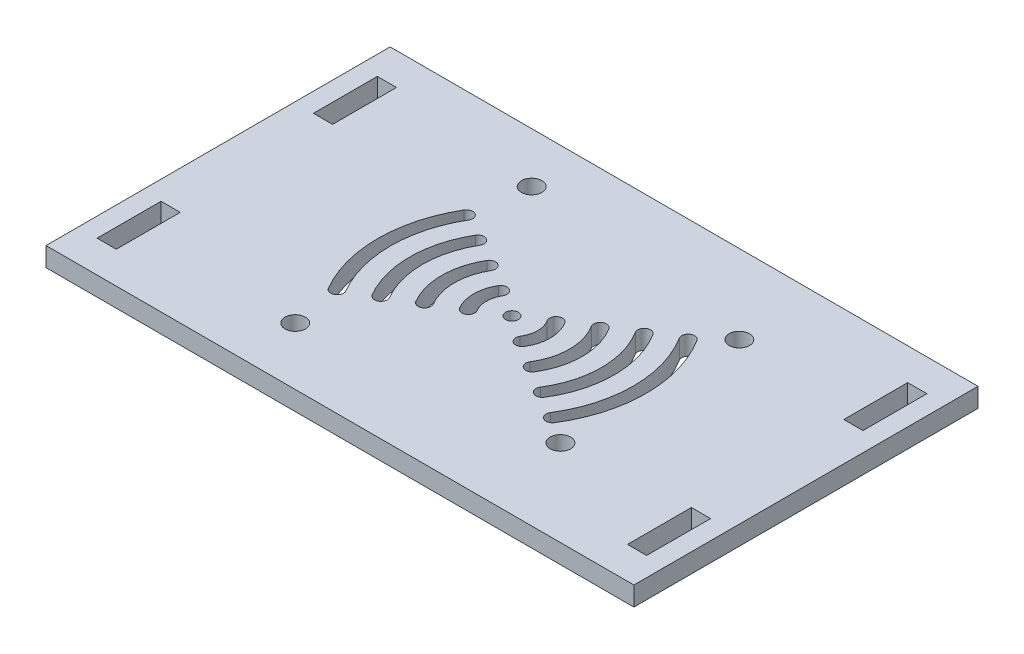
SolidWorks part; units mm, degrees
material "ABS"
ref_plane "Front Plane" through (0, 0, 0) normal (0, 0, 1) x (1, 0, 0)
ref_plane "Top Plane" through (0, 0, 0) normal (0, 1, 0) x (1, 0, 0)
ref_plane "Right Plane" through (0, 0, 0) normal (1, 0, 0) x (0, 0, -1)
sketch "Sketch1" plane through (0, 0, 0) normal (0, 1, 0) x (1, 0, 0)
  line L0 (0, 53.85) -> (92, 0) construction
  line L1 (0, 0) -> (92, 0)
  line L2 (0, 0) -> (0, 53.85)
  line L3 (0, 53.85) -> (92, 53.85)
  line L4 (92, 0) -> (92, 53.85)
  line L5 (3, 48.85) -> (6, 48.85)
  line L6 (3, 48.85) -> (3, 38.85)
  line L7 (3, 38.85) -> (6, 38.85)
  line L8 (6, 48.85) -> (6, 38.85)
  line L9 (3, 15) -> (6, 15)
  line L10 (3, 15) -> (3, 5)
  line L11 (3, 5) -> (6, 5)
  line L12 (6, 15) -> (6, 5)
  line L13 (92, 53.85) -> (0, 0) construction
  line L15 (86, 15) -> (86, 5)
  line L16 (89, 5) -> (86, 5)
  line L17 (89, 15) -> (89, 5)
  line L18 (89, 15) -> (86, 15)
  line L19 (86, 48.85) -> (86, 38.85)
  line L20 (89, 38.85) -> (86, 38.85)
  line L21 (89, 48.85) -> (89, 38.85)
  line L22 (89, 48.85) -> (86, 48.85)
  circle A0 centre (46, 26.925) radius 1
  arc A1 (41.6849, 29.4508) -> (41.6849, 24.3992) centre (46, 26.925) ccw construction
  arc A2 (40.8218, 29.9559) -> (40.8218, 23.8941) centre (46, 26.925) ccw
  arc A3 (42.5479, 28.9456) -> (42.5479, 24.9044) centre (46, 26.925) ccw
  arc A4 (42.5479, 28.9456) -> (40.8218, 29.9559) centre (41.6849, 29.4508) ccw
  arc A5 (40.8218, 23.8941) -> (42.5479, 24.9044) centre (41.6849, 24.3992) ccw
  arc A6 (37.3697, 21.8735) -> (37.3697, 31.9765) centre (46, 26.925) cw construction
  arc A7 (36.5067, 32.4817) -> (36.5067, 21.3683) centre (46, 26.925) ccw
  arc A8 (38.2327, 31.4714) -> (38.2327, 22.3786) centre (46, 26.925) ccw
  arc A9 (38.2327, 31.4714) -> (36.5067, 32.4817) centre (37.3697, 31.9765) ccw
  arc A10 (36.5067, 21.3683) -> (38.2327, 22.3786) centre (37.3697, 21.8735) ccw
  arc A11 (33.0546, 19.3477) -> (33.0546, 34.5023) centre (46, 26.925) cw construction
  arc A12 (32.1915, 35.0075) -> (32.1915, 18.8425) centre (46, 26.925) ccw
  arc A13 (33.9176, 33.9972) -> (33.9176, 19.8528) centre (46, 26.925) ccw
  arc A14 (33.9176, 33.9972) -> (32.1915, 35.0075) centre (33.0546, 34.5023) ccw
  arc A15 (32.1915, 18.8425) -> (33.9176, 19.8528) centre (33.0546, 19.3477) ccw
  arc A16 (28.7394, 16.8219) -> (28.7394, 37.0281) centre (46, 26.925) cw construction
  arc A17 (27.8764, 37.5332) -> (27.8764, 16.3168) centre (46, 26.925) ccw
  arc A18 (29.6024, 36.5229) -> (29.6024, 17.3271) centre (46, 26.925) ccw
  arc A19 (29.6024, 36.5229) -> (27.8764, 37.5332) centre (28.7394, 37.0281) ccw
  arc A20 (27.8764, 16.3168) -> (29.6024, 17.3271) centre (28.7394, 16.8219) ccw
  arc A21 (50.2378, 29.5785) -> (50.2378, 24.2715) centre (46, 26.925) cw construction
  arc A22 (51.0853, 30.1092) -> (51.0853, 23.7408) centre (46, 26.925) cw
  arc A23 (49.3902, 29.0478) -> (49.3902, 24.8022) centre (46, 26.925) cw
  arc A24 (49.3902, 29.0478) -> (51.0853, 30.1092) centre (50.2378, 29.5785) cw
  arc A25 (51.0853, 23.7408) -> (49.3902, 24.8022) centre (50.2378, 24.2715) cw
  arc A26 (54.4756, 21.6179) -> (54.4756, 32.2321) centre (46, 26.925) ccw construction
  arc A27 (55.3231, 32.7628) -> (55.3231, 21.0872) centre (46, 26.925) cw
  arc A28 (53.628, 31.7014) -> (53.628, 22.1486) centre (46, 26.925) cw
  arc A29 (53.628, 31.7014) -> (55.3231, 32.7628) centre (54.4756, 32.2321) cw
  arc A30 (55.3231, 21.0872) -> (53.628, 22.1486) centre (54.4756, 21.6179) cw
  arc A31 (58.7133, 18.9644) -> (58.7133, 34.8856) centre (46, 26.925) ccw construction
  arc A32 (59.5609, 35.4163) -> (59.5609, 18.4337) centre (46, 26.925) cw
  arc A33 (57.8658, 34.3549) -> (57.8658, 19.4951) centre (46, 26.925) cw
  arc A34 (57.8658, 34.3549) -> (59.5609, 35.4163) centre (58.7133, 34.8856) cw
  arc A35 (59.5609, 18.4337) -> (57.8658, 19.4951) centre (58.7133, 18.9644) cw
  arc A36 (62.9511, 16.3109) -> (62.9511, 37.5391) centre (46, 26.925) ccw construction
  arc A37 (63.7987, 38.0699) -> (63.7987, 15.7801) centre (46, 26.925) cw
  arc A38 (62.1035, 37.0084) -> (62.1035, 16.8416) centre (46, 26.925) cw
  arc A39 (62.1035, 37.0084) -> (63.7987, 38.0699) centre (62.9511, 37.5391) cw
  arc A40 (63.7987, 15.7801) -> (62.1035, 16.8416) centre (62.9511, 16.3109) cw
  circle A41 centre (30, 46) radius 1.6
  circle A42 centre (67, 41.5) radius 1.6
  circle A43 centre (67, 13.5) radius 1.6
  circle A44 centre (30, 9) radius 1.6
  point P27 (41, 26.925)
  point P32 (36, 26.925)
  point P40 (31, 26.925)
  point P48 (26, 26.925)
  point P58 (51, 26.925)
  point P65 (56, 26.925)
  point P72 (61, 26.925)
  point P79 (66, 26.925)
  point P90 (0, 0)
  point P91 (0, 0)
  point P92 (0, 0)
  point P95 (22.7247, 0)
  dimension "D11" = 2
  dimension "D12" = 1
  dimension "D13" = 1
  dimension "D14" = 1
  dimension "D15" = 1
  dimension "D28" = 3.2
  dimension "D1" = 53.85
  dimension "D2" = 92
  dimension "D3" = 10
  dimension "D4" = 3
  dimension "D5" = 3
  dimension "D6" = 3
  dimension "D7" = 3
  dimension "D8" = 10
  dimension "D9" = 5
  dimension "D10" = 5
  dimension "D16" = 5
  dimension "D17" = 10
  dimension "D18" = 15
  dimension "D19" = 20
  dimension "D20" = 3
  dimension "D21" = 3
  dimension "D22" = 10
  dimension "D23" = 10
  dimension "D24" = 3
  dimension "D25" = 3
  dimension "D26" = 5
  dimension "D27" = 5
  dimension "D29" = 37
  dimension "D30" = 28
  dimension "D31" = 37
  dimension "D32" = 4.5
  dimension "D33" = 30
  dimension "D34" = 9
extrude "Boss-Extrude1" add sketch "Sketch1" along normal blind 3
